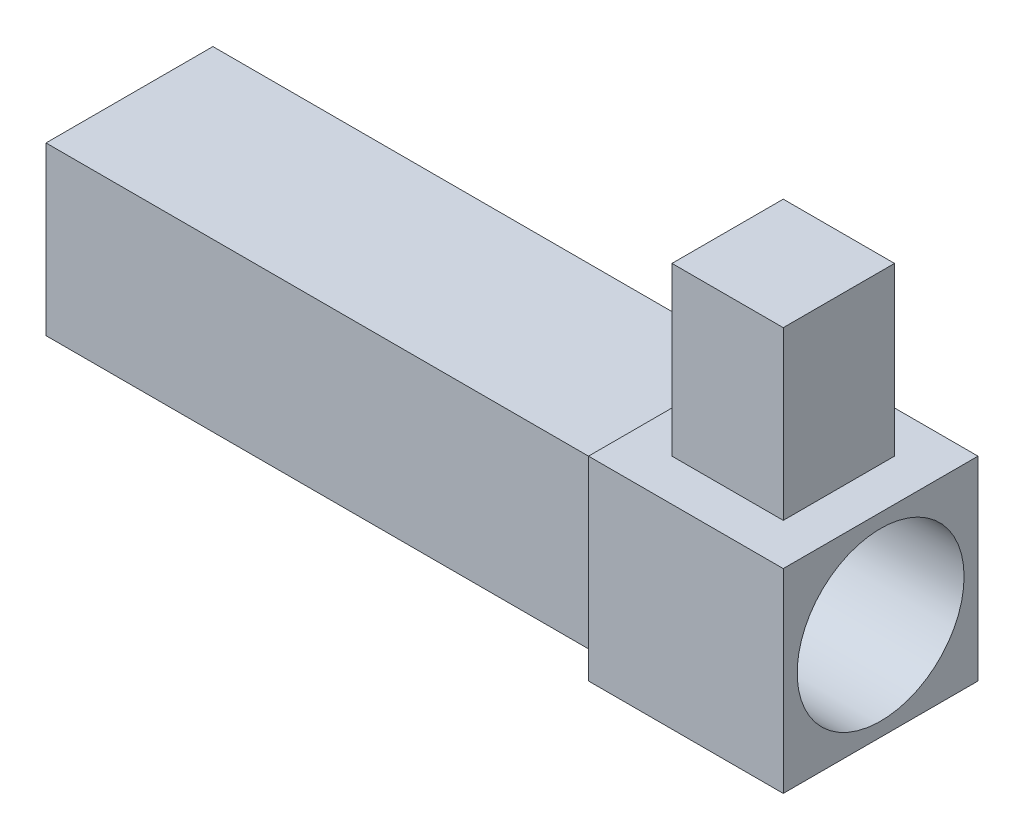
SolidWorks part; units mm, degrees
ref_plane "Front Plane" through (0, 0, 0) normal (0, 0, 1) x (1, 0, 0)
ref_plane "Top Plane" through (0, 0, 0) normal (0, 1, 0) x (1, 0, 0)
ref_plane "Right Plane" through (0, 0, 0) normal (1, 0, 0) x (0, 0, -1)
sketch "Sketch1" plane through (0, 0, 0) normal (1, 0, 0) x (0, 0, -1)
  line L1 (-15, 15) -> (15, 15)
  line L2 (-15, 15) -> (-15, -15)
  line L3 (-15, -15) -> (15, -15)
  line L4 (15, 15) -> (15, -15)
  line L5 (-15, 15) -> (15, -15) construction
  line L6 (-15, -15) -> (15, 15) construction
  point P0 (0, 0)
  dimension "D1" = 30
  dimension "D2" = 30
extrude "Boss-Extrude1" add sketch "Sketch1" along normal blind 100
sketch "Sketch2" plane through (100, 0, 0) normal (1, 0, 0) x (0, 0, -1)
  line L1 (-17.5, 17.5) -> (17.5, 17.5)
  line L2 (-17.5, 17.5) -> (-17.5, -17.5)
  line L3 (-17.5, -17.5) -> (17.5, -17.5)
  line L4 (17.5, 17.5) -> (17.5, -17.5)
  line L5 (-17.5, 17.5) -> (17.5, -17.5) construction
  line L6 (-17.5, -17.5) -> (17.5, 17.5) construction
  point P0 (0, 0)
  dimension "D1" = 35
  dimension "D2" = 35
extrude "Boss-Extrude2" add sketch "Sketch2" along normal blind 35
sketch "Sketch3" plane through (135, 0, 0) normal (1, 0, 0) x (0, 0, -1)
  circle A0 centre (0, 0) radius 15
  dimension "D1" = 30
extrude "Cut-Extrude1" cut sketch "Sketch3" against normal blind 30
sketch "Sketch4" plane through (0, 17.5, 0) normal (0, 1, 0) x (1, 0, 0)
  line L0 (117.5, 17.5) -> (117.5, -17.5) construction
  line L5 (135, 17.5) -> (100, 17.5) construction
  line L6 (135, -17.5) -> (100, -17.5) construction
  line L8 (107.5, 10) -> (127.5, 10)
  line L9 (107.5, 10) -> (107.5, -10)
  line L10 (107.5, -10) -> (127.5, -10)
  line L11 (127.5, 10) -> (127.5, -10)
  line L12 (107.5, 10) -> (127.5, -10) construction
  line L13 (107.5, -10) -> (127.5, 10) construction
  point P6 (117.5, 0)
  dimension "D1" = 20
  dimension "D2" = 20
extrude "Boss-Extrude3" add sketch "Sketch4" along normal blind 30
sketch "Sketch5" plane through (127.5, 0, 0) normal (1, 0, 0) x (0, 0, -1)
  line L1 (-2.3712, 46.5142) -> (2.6288, 46.5142)
  line L2 (-2.3712, 46.5142) -> (-2.3712, 41.5142)
  line L3 (-2.3712, 41.5142) -> (2.6288, 41.5142)
  line L4 (2.6288, 46.5142) -> (2.6288, 41.5142)
  line L5 (-2.3712, 46.5142) -> (2.6288, 41.5142) construction
  line L6 (-2.3712, 41.5142) -> (2.6288, 46.5142) construction
  point P0 (0.1288, 44.0142)
  dimension "D1" = 5
  dimension "D2" = 5
ref_point "Point2"
